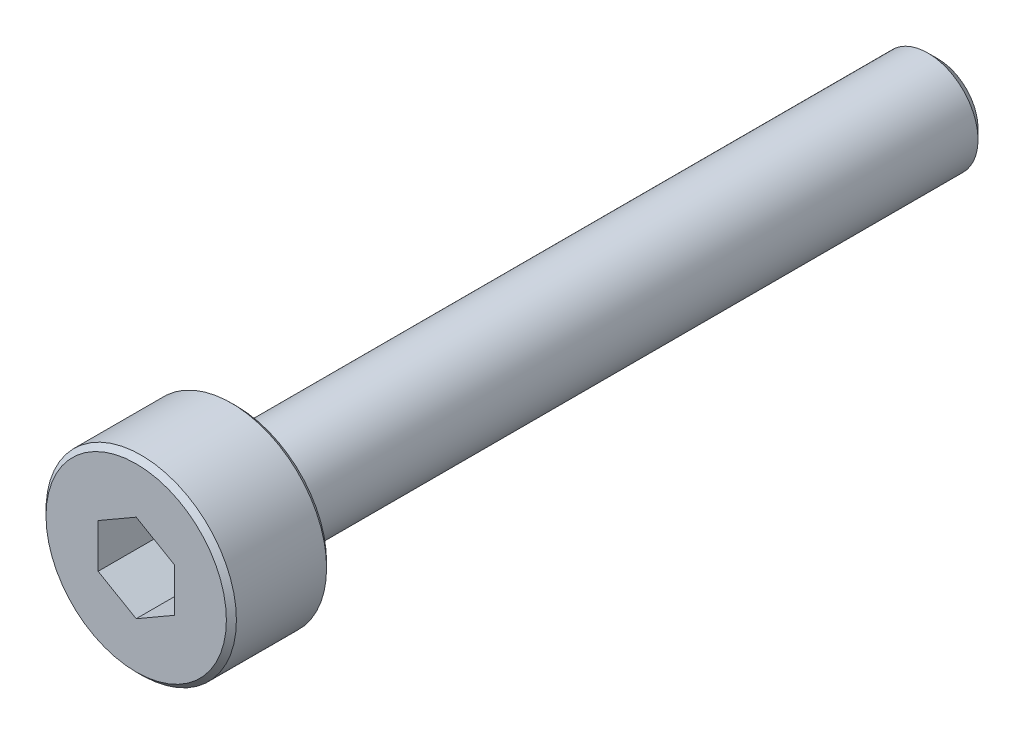
SolidWorks part; units mm, degrees
ref_plane "前视基准面" through (0, 0, 0) normal (0, 0, 1) x (1, 0, 0)
ref_plane "上视基准面" through (0, 0, 0) normal (0, 1, 0) x (1, 0, 0)
ref_plane "右视基准面" through (0, 0, 0) normal (1, 0, 0) x (0, 0, -1)
other "Configuration Table"
sketch "草图1" plane through (0, 0, 0) normal (0, 1, 0) x (1, 0, 0)
  line L0 (1.9, -10) -> (0, -10)
  line L1 (0, -10) -> (0, -12)
  line L2 (0, -12) -> (1.9, -12)
  line L3 (1.9, -12) -> (1.9, -10)
  line L4 (0, -10) -> (0, -12) construction
revolve "旋转1" add sketch "草图1" angle 360 about L4
sketch "草图2" plane through (0, 0, 10) normal (0, 0, -1) x (-1, 0, 0)
  circle A0 centre (0, 0) radius 1
extrude "凸台-拉伸1" add sketch "草图2" along normal blind 14
sketch "草图3" plane through (0, 0, 12) normal (0, 0, 1) x (1, 0, 0)
  line L0 (-0.76, -0.4388) -> (0, -0.8776)
  line L1 (0, -0.8776) -> (0.76, -0.4388)
  line L2 (0.76, -0.4388) -> (0.76, 0.4388)
  line L3 (0.76, 0.4388) -> (0, 0.8776)
  line L4 (0, 0.8776) -> (-0.76, 0.4388)
  line L5 (-0.76, 0.4388) -> (-0.76, -0.4388)
extrude "切除-拉伸1" cut sketch "草图3" against normal blind 1.5
chamfer "倒角1" distance 0.1 angle 45 2 edges at (1.9, 0, 10) (1.9, 0, 12)
chamfer "倒角2" distance 0.2 angle 45 1 edges at (-1, 0, -4)
